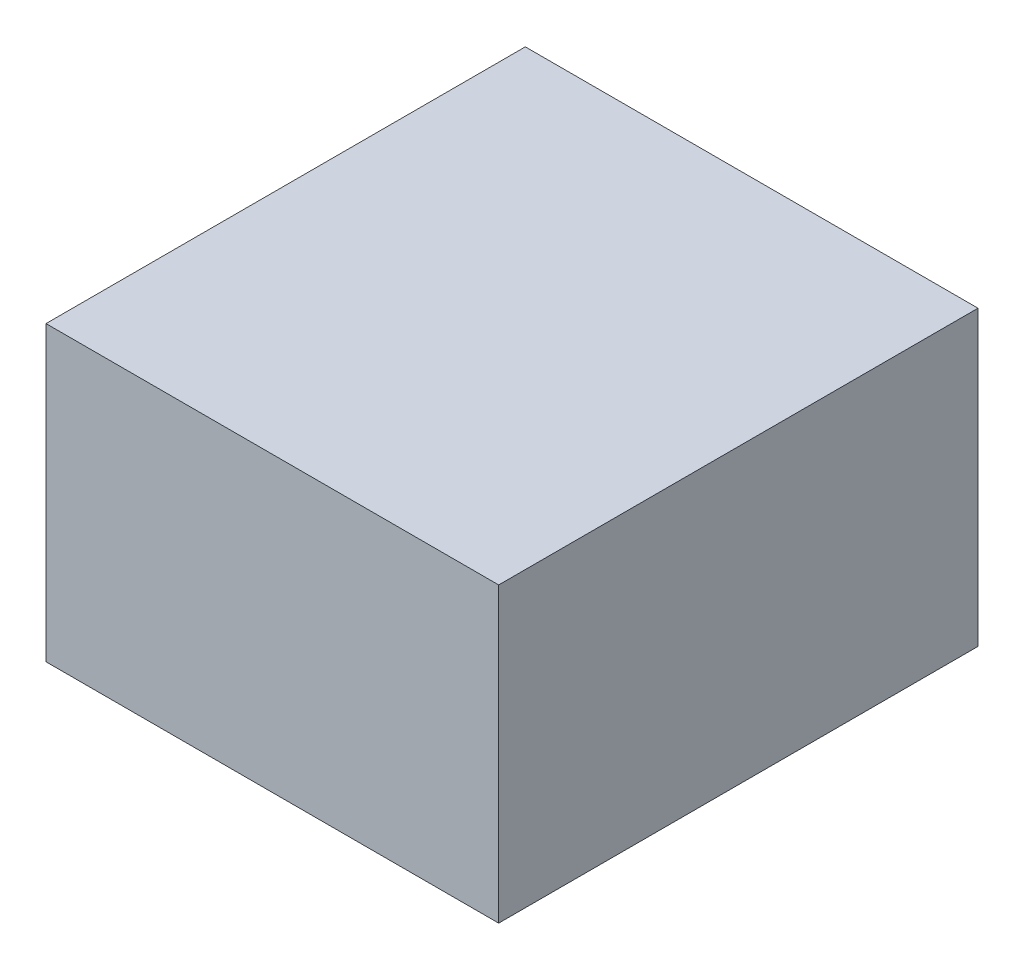
SolidWorks part; units mm, degrees
ref_plane "Alzado" through (0, 0, 0) normal (0, 0, 1) x (1, 0, 0)
ref_plane "Planta" through (0, 0, 0) normal (0, 1, 0) x (1, 0, 0)
ref_plane "Vista lateral" through (0, 0, 0) normal (1, 0, 0) x (0, 0, -1)
sketch "Croquis1" plane through (0, 0, 0) normal (0, 1, 0) x (1, 0, 0)
  line L1 (-170, 180) -> (170, 180)
  line L2 (-170, 180) -> (-170, -180)
  line L3 (-170, -180) -> (170, -180)
  line L4 (170, 180) -> (170, -180)
  dimension "D1" = 360
  dimension "D2" = 180
  dimension "D3" = 340
  dimension "D4" = 170
extrude "Saliente-Extruir1" add sketch "Croquis1" along normal blind 220
